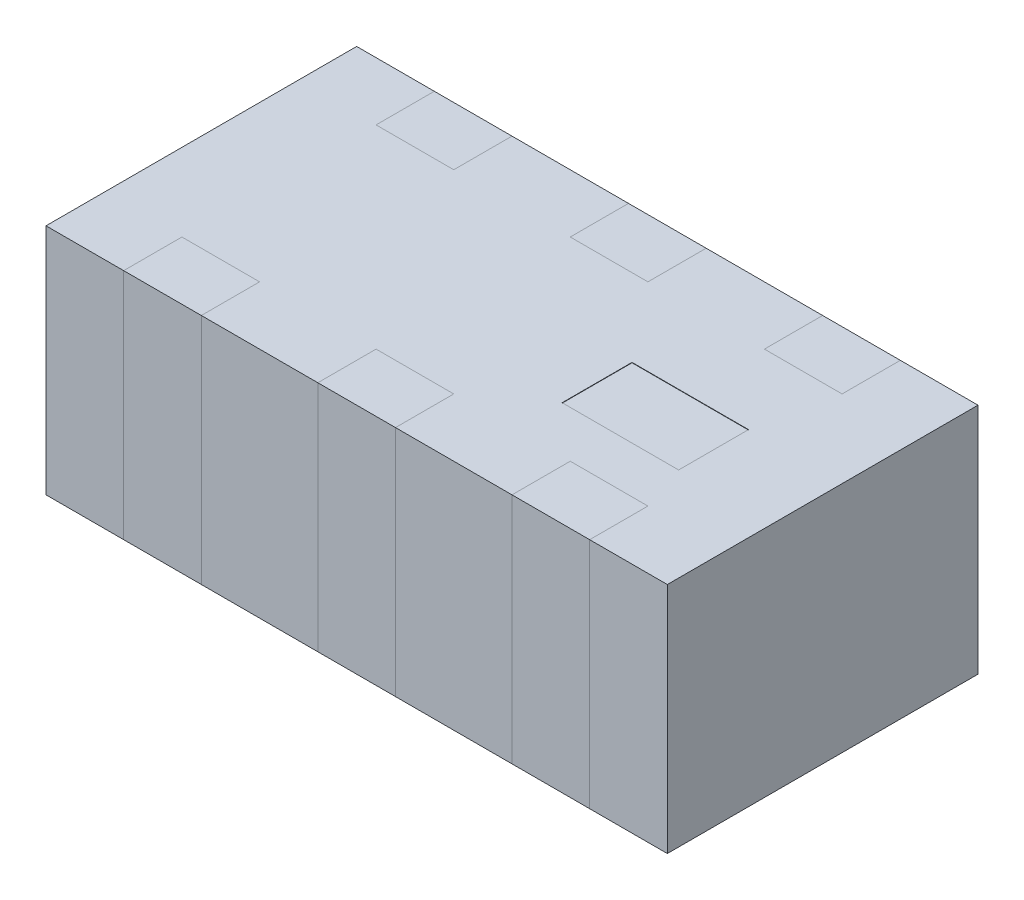
SolidWorks part; units mm, degrees
ref_plane "Front Plane" through (0, 0, 0) normal (0, 0, 1) x (1, 0, 0)
ref_plane "Top Plane" through (0, 0, 0) normal (0, 1, 0) x (1, 0, 0)
ref_plane "Right Plane" through (0, 0, 0) normal (1, 0, 0) x (0, 0, -1)
sketch "Sketch1" plane through (0, 0, 0) normal (0, 1, 0) x (1, 0, 0)
  line L1 (-0.8, 0.4) -> (0.8, 0.4)
  line L2 (-0.8, 0.4) -> (-0.8, -0.4)
  line L3 (-0.8, -0.4) -> (0.8, -0.4)
  line L4 (0.8, 0.4) -> (0.8, -0.4)
  line L5 (-0.8, 0.4) -> (0.8, -0.4) construction
  line L6 (-0.8, -0.4) -> (0.8, 0.4) construction
  point P0 (0, 0)
  dimension "D1" = 0.8
  dimension "D2" = 1.6
extrude "Boss-Extrude1" add sketch "Sketch1" along normal blind 0.6
sketch "Sketch2" plane through (0, 0.6, 0) normal (0, 1, 0) x (1, 0, 0)
  line L0 (-0.8, -0.4) -> (0.8, -0.4) construction
  line L1 (0.4, -0.4) -> (0.6, -0.4)
  line L2 (0.4, -0.4) -> (0.4, -0.25)
  line L3 (0.4, -0.25) -> (0.6, -0.25)
  line L4 (0.6, -0.4) -> (0.6, -0.25)
  line L5 (0.8, -0.4) -> (0.8, 0.4) construction
  line L6 (-0.1, -0.25) -> (0.1, -0.25)
  line L7 (0.1, -0.4) -> (0.1, -0.25)
  line L8 (-0.1, -0.4) -> (0.1, -0.4)
  line L9 (-0.1, -0.4) -> (-0.1, -0.25)
  line L10 (-0.6, -0.25) -> (-0.4, -0.25)
  line L11 (-0.4, -0.4) -> (-0.4, -0.25)
  line L12 (-0.6, -0.4) -> (-0.4, -0.4)
  line L13 (-0.6, -0.4) -> (-0.6, -0.25)
  line L15 (-0.9553, 0) -> (1.2338, 0) construction
  line L16 (-0.1, 0.4) -> (-0.1, 0.25)
  line L17 (-0.1, 0.4) -> (0.1, 0.4)
  line L18 (0.1, 0.4) -> (0.1, 0.25)
  line L19 (-0.1, 0.25) -> (0.1, 0.25)
  line L20 (0.6, 0.4) -> (0.6, 0.25)
  line L21 (0.4, 0.25) -> (0.6, 0.25)
  line L22 (0.4, 0.4) -> (0.4, 0.25)
  line L23 (0.4, 0.4) -> (0.6, 0.4)
  line L24 (-0.6, 0.4) -> (-0.4, 0.4)
  line L25 (-0.4, 0.4) -> (-0.4, 0.25)
  line L26 (-0.6, 0.4) -> (-0.6, 0.25)
  line L27 (-0.6, 0.25) -> (-0.4, 0.25)
  point P9 (0.1, -0.325)
  dimension "D1" = 0.15
  dimension "D2" = 0.2
  dimension "D3" = 0.2
  dimension "D5" = 0.3
  dimension "D4" = 3
extrude "Cut-Extrude1" cut sketch "Sketch2" against normal blind 1
sketch "Sketch3" plane through (0, 0.6, 0) normal (0, 1, 0) x (1, 0, 0)
  line L0 (-0.6, 0.4) -> (-0.4, 0.4)
  line L1 (0.6, -0.4) -> (0.4, -0.4)
  line L2 (-0.4, -0.4) -> (-0.6, -0.4)
  line L3 (0.1, -0.4) -> (-0.1, -0.4)
  line L4 (0.4, 0.4) -> (0.6, 0.4)
  line L5 (-0.1, 0.4) -> (0.1, 0.4)
  line L28 (-0.1, -0.4) -> (-0.1, -0.25)
  line L29 (-0.1, -0.25) -> (0.1, -0.25)
  line L30 (0.1, -0.25) -> (0.1, -0.4)
  line L31 (0.1, -0.4) -> (0.4, -0.4)
  line L32 (0.4, -0.4) -> (0.4, -0.25)
  line L33 (0.4, -0.25) -> (0.6, -0.25)
  line L34 (0.6, -0.25) -> (0.6, -0.4)
  line L35 (0.6, -0.4) -> (0.8, -0.4)
  line L36 (0.8, -0.4) -> (0.8, 0.4)
  line L37 (0.8, 0.4) -> (0.6, 0.4)
  line L38 (0.6, 0.4) -> (0.6, 0.25)
  line L39 (0.6, 0.25) -> (0.4, 0.25)
  line L40 (0.4, 0.25) -> (0.4, 0.4)
  line L41 (0.4, 0.4) -> (0.1, 0.4)
  line L42 (0.1, 0.4) -> (0.1, 0.25)
  line L43 (0.1, 0.25) -> (-0.1, 0.25)
  line L44 (-0.1, 0.25) -> (-0.1, 0.4)
  line L45 (-0.1, 0.4) -> (-0.4, 0.4)
  line L46 (-0.4, 0.4) -> (-0.4, 0.25)
  line L47 (-0.4, 0.25) -> (-0.6, 0.25)
  line L48 (-0.6, 0.25) -> (-0.6, 0.4)
  line L49 (-0.6, 0.4) -> (-0.8, 0.4)
  line L50 (-0.8, 0.4) -> (-0.8, -0.4)
  line L51 (-0.8, -0.4) -> (-0.6, -0.4)
  line L52 (-0.6, -0.4) -> (-0.6, -0.25)
  line L53 (-0.6, -0.25) -> (-0.4, -0.25)
  line L54 (-0.4, -0.25) -> (-0.4, -0.4)
  line L55 (-0.4, -0.4) -> (-0.1, -0.4)
  line L56 (-0.1, -0.4) -> (-0.1, -0.25)
  line L57 (-0.1, -0.25) -> (0.1, -0.25)
  line L58 (0.1, -0.25) -> (0.1, -0.4)
  line L60 (0.4, -0.4) -> (0.4, -0.25)
  line L61 (0.4, -0.25) -> (0.6, -0.25)
  line L62 (0.6, -0.25) -> (0.6, -0.4)
  line L66 (0.6, 0.4) -> (0.6, 0.25)
  line L67 (0.6, 0.25) -> (0.4, 0.25)
  line L68 (0.4, 0.25) -> (0.4, 0.4)
  line L70 (0.1, 0.4) -> (0.1, 0.25)
  line L71 (0.1, 0.25) -> (-0.1, 0.25)
  line L72 (-0.1, 0.25) -> (-0.1, 0.4)
  line L74 (-0.4, 0.4) -> (-0.4, 0.25)
  line L75 (-0.4, 0.25) -> (-0.6, 0.25)
  line L76 (-0.6, 0.25) -> (-0.6, 0.4)
  line L80 (-0.6, -0.4) -> (-0.6, -0.25)
  line L81 (-0.6, -0.25) -> (-0.4, -0.25)
  line L82 (-0.4, -0.25) -> (-0.4, -0.4)
  dimension "D1" = 0
extrude "Boss-Extrude3" add sketch "Sketch3" against normal up to surface (0.6 mm away) separate body up to face at (0, 0, 0)
sketch "Sketch4" plane through (0, 0.6, 0) normal (0, 1, 0) x (1, 0, 0)
  line L0 (-0.4943, 0) -> (0.9946, 0) construction
  line L1 (0.2591, 0.05) -> (0.5591, 0.05)
  line L2 (0.2591, 0.05) -> (0.2591, -0.13)
  line L3 (0.2591, -0.13) -> (0.5591, -0.13)
  line L4 (0.5591, 0.05) -> (0.5591, -0.13)
  line L5 (0.4, 0.25) -> (0.6, 0.25) construction
  point P7 (0, 0)
  point P8 (0, 0)
  point P9 (0, 0)
  dimension "D1" = 0.18
  dimension "D2" = 0.3
  dimension "D3" = 0.2
extrude "Cut-Extrude2" cut sketch "Sketch4" against normal blind 0.001
